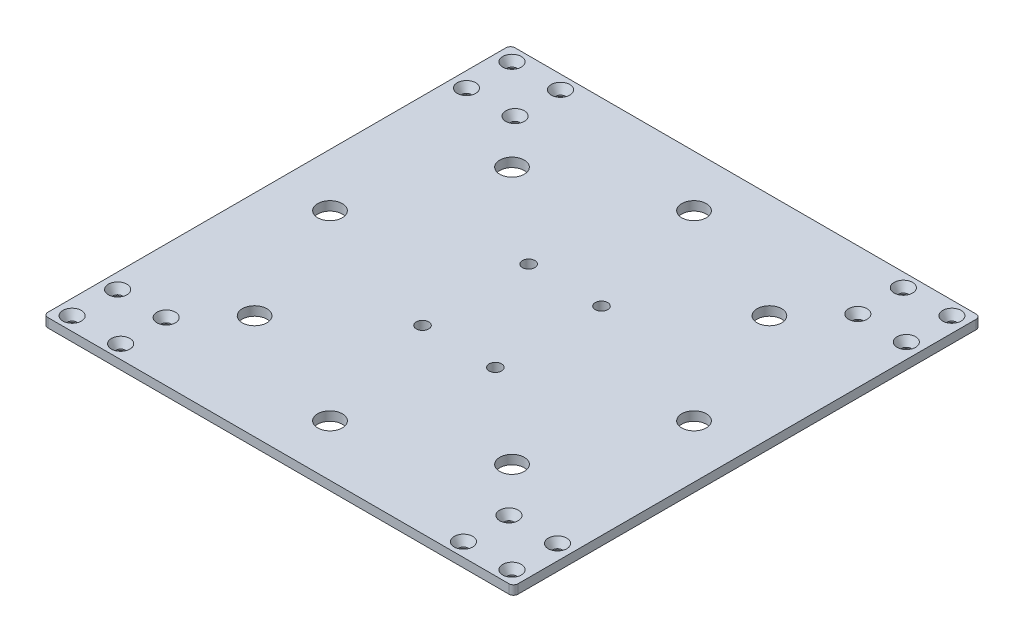
SolidWorks part; units mm, degrees
material "Thornel Mat VMA"
ref_plane "前视基准面" through (0, 0, 0) normal (0, 0, 1) x (1, 0, 0)
ref_plane "上视基准面" through (0, 0, 0) normal (0, 1, 0) x (1, 0, 0)
ref_plane "右视基准面" through (0, 0, 0) normal (1, 0, 0) x (0, 0, -1)
sketch "草图1" plane through (0, 0, 0) normal (0, 1, 0) x (1, 0, 0)
  line L0 (-56.4902, 65) -> (96.6288, 65) construction
  line L1 (-12, 17.5) -> (12, 17.5) construction
  line L2 (-12, 17.5) -> (-12, -17.5) construction
  line L3 (-12, -17.5) -> (12, -17.5) construction
  line L4 (12, 17.5) -> (12, -17.5) construction
  line L5 (0, -17.5) -> (0, 17.5) construction
  line L6 (-12, 0) -> (12, 0) construction
  line L7 (-56.5, 57.5) -> (-72.5, 57.5) construction
  line L8 (56.5, 72.5) -> (72.5, 72.5) construction
  line L9 (56.5, 72.5) -> (56.5, 57.5) construction
  line L10 (56.5, 57.5) -> (72.5, 57.5) construction
  line L11 (72.5, 72.5) -> (72.5, 57.5) construction
  line L12 (64.5, 57.5) -> (64.5, 72.5) construction
  line L13 (56.5, 65) -> (72.5, 65) construction
  line L14 (-77.5, 77) -> (77.5, 77)
  line L15 (-77.5, 77) -> (-77.5, -77)
  line L16 (-77.5, -77) -> (77.5, -77)
  line L17 (77.5, 77) -> (77.5, -77)
  line L18 (0, -77) -> (0, 77) construction
  line L19 (-77.5, 0) -> (77.5, 0) construction
  line L20 (-72.5, 72.5) -> (-72.5, 57.5) construction
  line L21 (-56.5, 72.5) -> (-72.5, 72.5) construction
  line L22 (-56.5, 72.5) -> (-56.5, 57.5) construction
  line L23 (56.5, -57.5) -> (72.5, -57.5) construction
  line L24 (72.5, -72.5) -> (72.5, -57.5) construction
  line L25 (56.5, -72.5) -> (72.5, -72.5) construction
  line L26 (56.5, -72.5) -> (56.5, -57.5) construction
  line L27 (-56.5, -72.5) -> (-56.5, -57.5) construction
  line L28 (-56.5, -72.5) -> (-72.5, -72.5) construction
  line L29 (-72.5, -72.5) -> (-72.5, -57.5) construction
  line L30 (-56.5, -57.5) -> (-72.5, -57.5) construction
  circle A0 centre (56.5, 72.5) radius 1.55
  circle A1 centre (72.5, 72.5) radius 1.55
  circle A2 centre (72.5, 57.5) radius 1.55
  circle A3 centre (56.5, 57.5) radius 1.55
  circle A4 centre (-56.5, 57.5) radius 1.55
  circle A5 centre (-72.5, 57.5) radius 1.55
  circle A6 centre (-72.5, 72.5) radius 1.55
  circle A7 centre (-56.5, 72.5) radius 1.55
  circle A8 centre (56.5, -57.5) radius 1.55
  circle A9 centre (72.5, -57.5) radius 1.55
  circle A10 centre (72.5, -72.5) radius 1.55
  circle A11 centre (56.5, -72.5) radius 1.55
  circle A12 centre (-56.5, -57.5) radius 1.55
  circle A13 centre (-72.5, -57.5) radius 1.55
  circle A14 centre (-56.5, -72.5) radius 1.55
  circle A15 centre (-72.5, -72.5) radius 1.55
  circle A16 centre (-12, 17.5) radius 2.05
  circle A17 centre (12, 17.5) radius 2.05
  circle A18 centre (12, -17.5) radius 2.05
  circle A19 centre (-12, -17.5) radius 2.05
  circle A20 centre (0, 0) radius 60 construction
  circle A26 centre (60, 0) radius 4.05
  circle A27 centre (42.4264, -42.4264) radius 4.05
  circle A28 centre (0, -60) radius 4.05
  circle A29 centre (-42.4264, -42.4264) radius 4.05
  circle A30 centre (-60, 0) radius 4.05
  circle A31 centre (-42.4264, 42.4264) radius 4.05
  circle A32 centre (0, 60) radius 4.05
  circle A33 centre (42.4264, 42.4264) radius 4.05
  point P32 (0, 0)
  point P50 (64.5, 65)
  point P75 (0, 0)
  point P80 (0, 0)
  point P85 (0, 0)
  dimension "D9" = 3.1
  dimension "D10" = 4.1
  dimension "D11" = 120
  dimension "D12" = 8.1
  dimension "D6" = 145
  dimension "D1" = 24
  dimension "D2" = 35
  dimension "D3" = 12
  dimension "D4" = 16
  dimension "D5" = 15
  dimension "D7" = 155
  dimension "D8" = 5
  dimension "D13" = 8
extrude "凸台-拉伸1" add sketch "草图1" along normal blind 3
fillet "圆角1" radius 1.5 4 edges at (-77.5, 1.5, -77) (77.5, 1.5, -77) (77.5, 1.5, 77) (-77.5, 1.5, 77)
chamfer "倒角1" distance 1.5 angle 60 16 edges at (-72.5, 3, 74.05) (-56.5, 3, 74.05) (-56.5, 3, 55.95) (-72.5, 3, 55.95) (72.5, 3, 70.95) (56.5, 3, 70.95) (72.5, 3, 59.05) (56.5, 3, 59.05) (72.5, 3, -59.05) (56.5, 3, -59.05) (72.5, 3, -70.95) (56.5, 3, -70.95) (-56.5, 3, -55.95) (-72.5, 3, -55.95) (-56.5, 3, -74.05) (-72.5, 3, -74.05)
